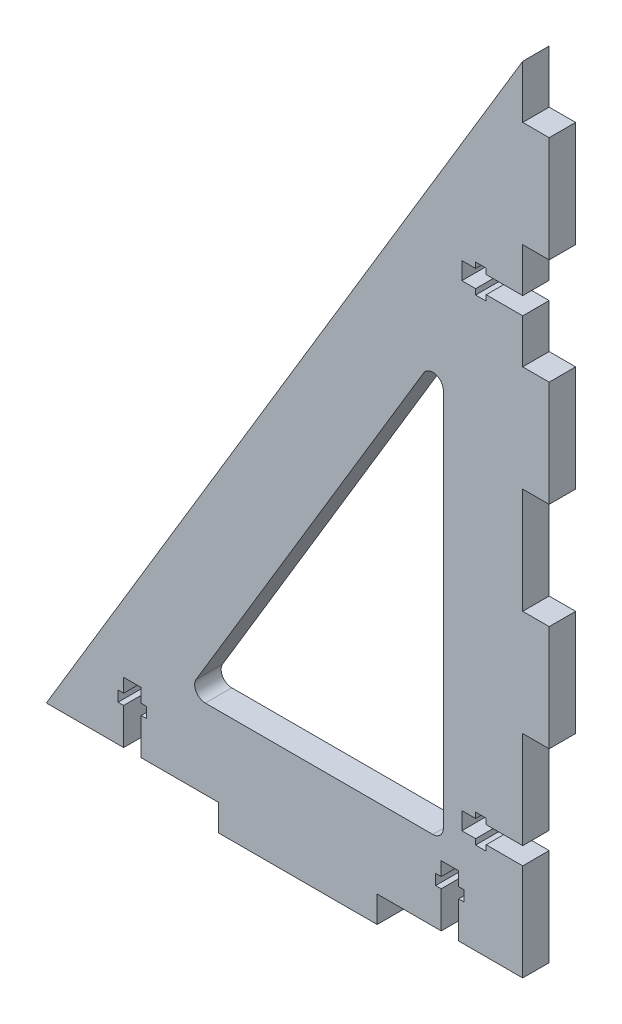
SolidWorks part; units mm, degrees
ref_plane "Front Plane" through (0, 0, 0) normal (0, 0, 1) x (1, 0, 0)
ref_plane "Top Plane" through (0, 0, 0) normal (0, 1, 0) x (1, 0, 0)
ref_plane "Right Plane" through (0, 0, 0) normal (1, 0, 0) x (0, 0, -1)
sketch "Sketch1" plane through (0, 0, 0) normal (0, 0, 1) x (1, 0, 0)
  line L0 (0, 190.5) -> (0, 0)
  line L2 (0, 0) -> (-114.3, 0)
  line L3 (-114.3, 0) -> (0, 190.5)
  dimension "D1" = 190.5
  dimension "D2" = 114.3
extrude "Boss-Extrude1" add sketch "Sketch1" along normal mid plane 6.35
sketch "Sketch2" plane through (0, 0, 3.175) normal (0, 0, 1) x (1, 0, 0)
  line L9 (-80.6541, 19.05) -> (-19.05, 19.05)
  line L10 (-19.05, 19.05) -> (-19.05, 121.7235)
  line L11 (-19.05, 121.7235) -> (-80.6541, 19.05)
  line L12 (-80.6541, 19.05) -> (-19.05, 19.05)
  line L13 (-19.05, 19.05) -> (-19.05, 121.7235)
  line L14 (-19.05, 121.7235) -> (-80.6541, 19.05)
  dimension "D1" = 19.05
extrude "Cut-Extrude1" cut sketch "Sketch2" against normal through all
sketch "Sketch4" plane through (0, 0, 0) normal (1, 0, 0) x (0, 0, -1)
  line L0 (-3.175, 0) -> (-3.175, 190.5) construction
  line L1 (-3.175, 177.8) -> (3.175, 177.8)
  line L2 (-3.175, 177.8) -> (-3.175, 152.4)
  line L3 (-3.175, 152.4) -> (3.175, 152.4)
  line L4 (3.175, 177.8) -> (3.175, 152.4)
  line L5 (3.175, 0) -> (3.175, 190.5) construction
  dimension "D1" = 25.4
  dimension "D2" = 12.7
extrude "Boss-Extrude2" add sketch "Sketch4" along normal blind 6.35
pattern_linear "LPattern1" count 3 spacing 50.8 along (0, -1, 0) of "Boss-Extrude2"
sketch "Sketch5" plane through (0, 0, 0) normal (0, -1, 0) x (-1, 0, 0)
  line L0 (114.3, -3.175) -> (0, -3.175) construction
  line L1 (73.025, -3.175) -> (34.925, -3.175)
  line L2 (73.025, -3.175) -> (73.025, 3.175)
  line L3 (73.025, 3.175) -> (34.925, 3.175)
  line L4 (34.925, -3.175) -> (34.925, 3.175)
  line L5 (114.3, 3.175) -> (0, 3.175) construction
  line L6 (53.975, -27.772) -> (53.975, 19.1203) construction
  line L7 (114.3, -3.175) -> (114.3, 3.175) construction
  line L8 (-6.35, -3.175) -> (-6.35, 3.175) construction
  dimension "D1" = 38.1
extrude "Boss-Extrude3" add sketch "Sketch5" along normal blind 6.35
fillet "Fillet1" radius 2.54 3 edges at (-19.05, 121.7235, 0) (-19.05, 19.05, 0) (-80.6541, 19.05, 0)
sketch "Sketch3" plane through (0, 0, -3.175) normal (0, 0, -1) x (-1, 0, 0)
  line L1 (114.3, 0) -> (73.025, 0) construction
  line L3 (0, 25.4) -> (14.605, 25.4) construction
  line L4 (17.4625, 0) -> (17.4625, 14.605) construction
  line L5 (93.6625, 0) -> (93.6625, 14.605) construction
  line L6 (0, 0) -> (0, 50.8) construction
  line L7 (114.3, 0) -> (73.025, 0) construction
  line L10 (-6.35, 152.4) -> (0, 152.4) construction
  line L11 (-6.35, 127) -> (0, 127) construction
  line L12 (34.925, 0) -> (0, 0) construction
  line L13 (-6.35, 50.8) -> (0, 50.8) construction
  line L14 (0, 0) -> (0, 50.8) construction
  line L15 (34.925, -6.35) -> (34.925, 0) construction
  line L16 (114.3, 0) -> (114.3, 37.2024) construction
  line L17 (73.025, -6.35) -> (73.025, 0) construction
  line B0 (91.567, 0) -> (95.758, 0)
  line B1 (95.758, 11.303) -> (97.0915, 11.303)
  line B2 (97.0915, 11.303) -> (97.0915, 8.763)
  line B3 (97.0915, 8.763) -> (95.758, 8.763)
  line B4 (95.758, 8.763) -> (95.758, 0)
  line B5 (95.758, 11.303) -> (95.758, 14.605)
  line B6 (95.758, 14.605) -> (91.567, 14.605)
  line B7 (91.567, 11.303) -> (91.567, 14.605)
  line B8 (91.567, 8.763) -> (91.567, 0)
  line B9 (90.2335, 8.763) -> (91.567, 8.763)
  line B10 (90.2335, 11.303) -> (90.2335, 8.763)
  line B11 (91.567, 11.303) -> (90.2335, 11.303)
  line B12 (15.367, 0) -> (19.558, 0)
  line B13 (19.558, 11.303) -> (20.8915, 11.303)
  line B14 (20.8915, 11.303) -> (20.8915, 8.763)
  line B15 (20.8915, 8.763) -> (19.558, 8.763)
  line B16 (19.558, 8.763) -> (19.558, 0)
  line B17 (19.558, 11.303) -> (19.558, 14.605)
  line B18 (19.558, 14.605) -> (15.367, 14.605)
  line B19 (15.367, 11.303) -> (15.367, 14.605)
  line B20 (15.367, 8.763) -> (15.367, 0)
  line B21 (14.0335, 8.763) -> (15.367, 8.763)
  line B22 (14.0335, 11.303) -> (14.0335, 8.763)
  line B23 (15.367, 11.303) -> (14.0335, 11.303)
  line B24 (0, 141.7955) -> (0, 137.6045)
  line B25 (11.303, 137.6045) -> (11.303, 136.271)
  line B26 (11.303, 136.271) -> (8.763, 136.271)
  line B27 (8.763, 136.271) -> (8.763, 137.6045)
  line B28 (8.763, 137.6045) -> (0, 137.6045)
  line B29 (11.303, 137.6045) -> (14.605, 137.6045)
  line B30 (14.605, 137.6045) -> (14.605, 141.7955)
  line B31 (11.303, 141.7955) -> (14.605, 141.7955)
  line B32 (8.763, 141.7955) -> (0, 141.7955)
  line B33 (8.763, 143.129) -> (8.763, 141.7955)
  line B34 (11.303, 143.129) -> (8.763, 143.129)
  line B35 (11.303, 141.7955) -> (11.303, 143.129)
  line B36 (0, 139.7) -> (14.605, 139.7) construction
  line B37 (0, 27.4955) -> (0, 23.3045)
  line B38 (11.303, 23.3045) -> (11.303, 21.971)
  line B39 (11.303, 21.971) -> (8.763, 21.971)
  line B40 (8.763, 21.971) -> (8.763, 23.3045)
  line B41 (8.763, 23.3045) -> (0, 23.3045)
  line B42 (11.303, 23.3045) -> (14.605, 23.3045)
  line B43 (14.605, 23.3045) -> (14.605, 27.4955)
  line B44 (11.303, 27.4955) -> (14.605, 27.4955)
  line B45 (8.763, 27.4955) -> (0, 27.4955)
  line B46 (8.763, 28.829) -> (8.763, 27.4955)
  line B47 (11.303, 28.829) -> (8.763, 28.829)
  line B48 (11.303, 27.4955) -> (11.303, 28.829)
sketch_block_instance "TSlot-1"
sketch_block "TSlot" parameters "D1"=3.302, "D2"=2.54, "D3"=3.175, "D4"=8.763, "D5"=1.3462
sketch_block_instance "TSlot-3"
sketch_block_instance "TSlot-4"
sketch_block_instance "TSlot-5"
extrude "Cut-Extrude2" cut sketch "Sketch3" against normal blind 6.35
